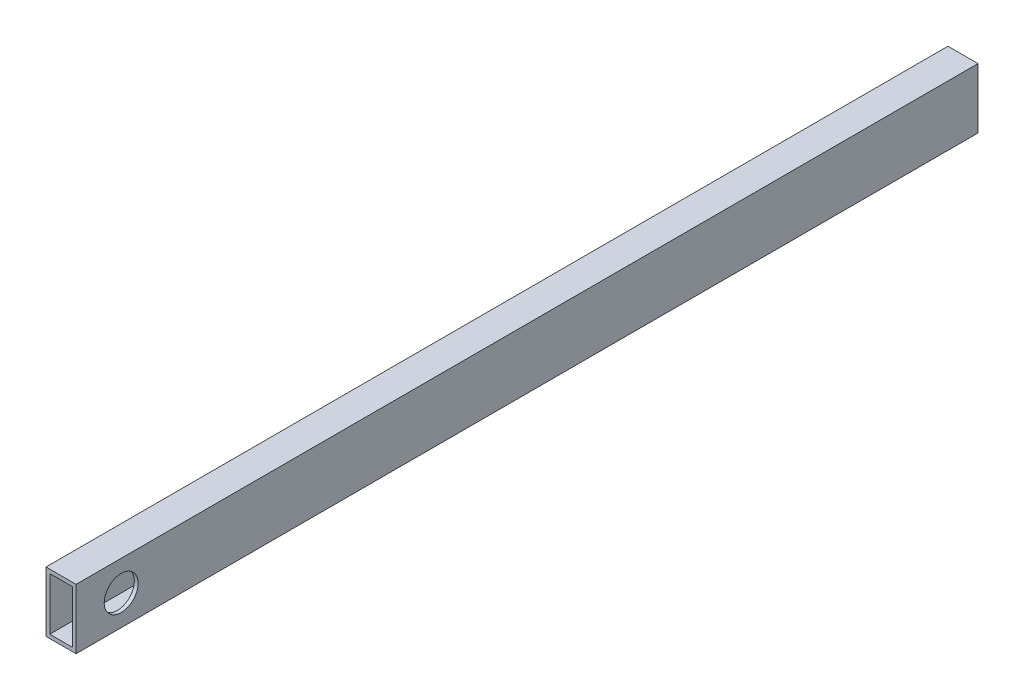
SolidWorks part; units mm, degrees
ref_plane "Front Plane" through (0, 0, 0) normal (0, 0, 1) x (1, 0, 0)
ref_plane "Top Plane" through (0, 0, 0) normal (0, 1, 0) x (1, 0, 0)
ref_plane "Right Plane" through (0, 0, 0) normal (1, 0, 0) x (0, 0, -1)
sketch "Sketch1" plane through (0, 0, 0) normal (0, 0, 1) x (1, 0, 0)
  line L0 (-9.525, 22.225) -> (9.525, 22.225)
  line L1 (-12.7, -25.4) -> (12.7, -25.4)
  line L2 (-12.7, -25.4) -> (-12.7, 25.4)
  line L3 (-12.7, 25.4) -> (12.7, 25.4)
  line L4 (12.7, -25.4) -> (12.7, 25.4)
  line L5 (-12.7, -25.4) -> (12.7, 25.4) construction
  line L6 (-12.7, 25.4) -> (12.7, -25.4) construction
  line L7 (9.525, -22.225) -> (9.525, 22.225)
  line L8 (-9.525, -22.225) -> (9.525, -22.225)
  line L9 (-9.525, -22.225) -> (-9.525, 22.225)
  point P0 (0, 0)
  dimension "D1" = 25.4
  dimension "D2" = 50.8
  dimension "D3" = 3.175
extrude "Boss-Extrude1" add sketch "Sketch1" along normal blind 762
sketch "Sketch2" plane through (-12.7, 0, 0) normal (-1, 0, 0) x (0, 0, 1)
  line L0 (762, 25.4) -> (0, 25.4) construction
  line L1 (762, 25.4) -> (762, -25.4) construction
  circle A0 centre (723.9, 0) radius 14.3129
  dimension "D2" = 28.6258
  dimension "D1" = 25.4
  dimension "D3" = 38.1
extrude "Cut-Extrude1" cut sketch "Sketch2" against normal through all
